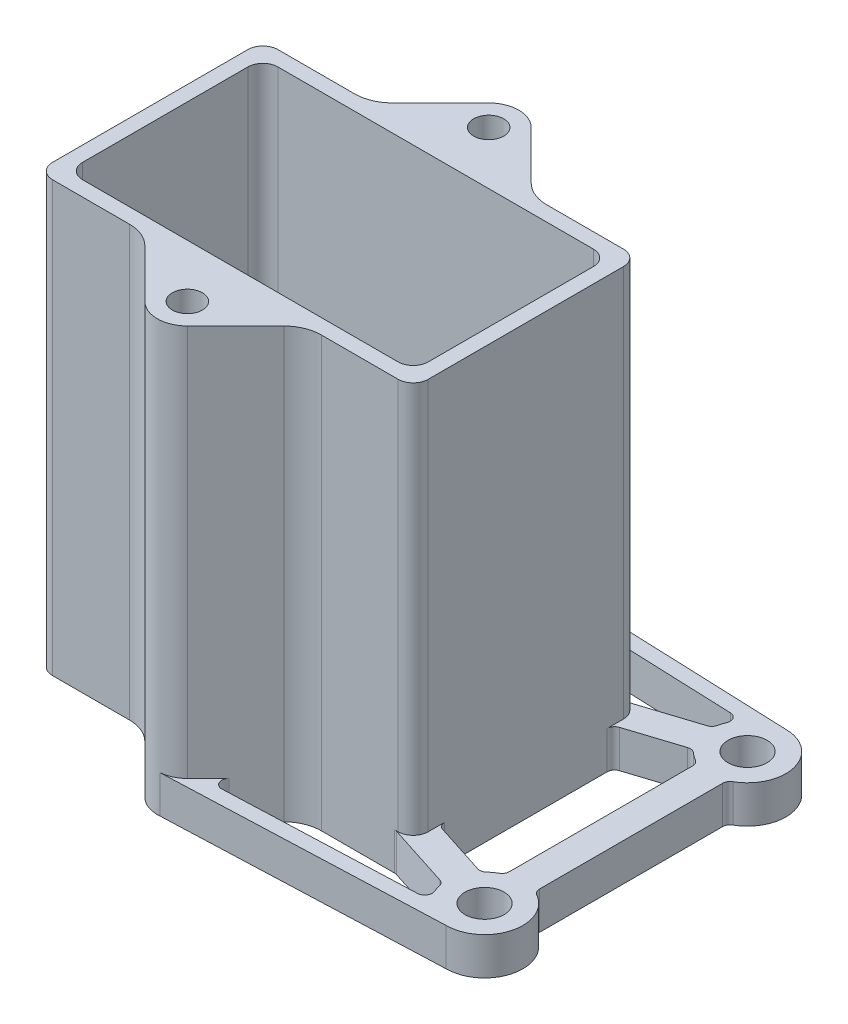
SolidWorks part; units mm, degrees
ref_plane "Front Plane" through (0, 0, 0) normal (0, 0, 1) x (1, 0, 0)
ref_plane "Top Plane" through (0, 0, 0) normal (0, 1, 0) x (1, 0, 0)
ref_plane "Right Plane" through (0, 0, 0) normal (1, 0, 0) x (0, 0, -1)
sketch "Sketch1" plane through (0, 0, 0) normal (0, 1, 0) x (1, 0, 0)
  line L1 (-25, -15) -> (25, -15)
  line L2 (-25, -15) -> (-25, 15)
  line L3 (-25, 15) -> (25, 15)
  line L4 (25, -15) -> (25, 15)
  line L5 (-25, -15) -> (25, 15) construction
  line L6 (-25, 15) -> (25, -15) construction
  point P0 (0, 0)
  dimension "D1" = 30
  dimension "D2" = 50
extrude "Boss-Extrude1" add sketch "Sketch1" along normal blind 3
sketch "Sketch2" plane through (0, 3, 0) normal (0, 1, 0) x (1, 0, 0)
  line L0 (23, -13) -> (23, 13)
  line L1 (23, 13) -> (-23, 13)
  line L2 (-23, 13) -> (-23, -13)
  line L3 (-23, -13) -> (23, -13)
  line L4 (25, -15) -> (25, 15)
  line L5 (25, 15) -> (-25, 15)
  line L6 (-25, 15) -> (-25, -15)
  line L7 (-25, -15) -> (25, -15)
  line L8 (25, -15) -> (25, 15)
  line L9 (25, 15) -> (-25, 15)
  line L10 (-25, 15) -> (-25, -15)
  line L11 (-25, -15) -> (25, -15)
  dimension "D1" = 0
  dimension "D2" = 2
extrude "Boss-Extrude2" add sketch "Sketch2" along normal blind 54.15
sketch "Sketch3" plane through (0, 0, 0) normal (0, 1, 0) x (1, 0, 0)
  line L0 (0, 0) -> (0, 20.05) construction
  line L1 (-2.8284, 22.8784) -> (-10.7069, 15)
  line L2 (-10.7069, 15) -> (10.7069, 15)
  line L3 (10.7069, 15) -> (2.8284, 22.8784)
  line L4 (25, -15) -> (25, 15)
  line L5 (-25, -15) -> (25, -15)
  line L6 (-25, 15) -> (-25, -15)
  line L7 (25, 15) -> (-25, 15)
  line L8 (25, -15) -> (25, 15)
  line L9 (-25, -15) -> (25, -15)
  line L10 (-25, 15) -> (-25, -15)
  line L11 (25, 15) -> (-25, 15)
  arc A0 (2.8284, 22.8784) -> (-2.8284, 22.8784) centre (0, 20.05) ccw
  circle A1 centre (0, 20.05) radius 2
  dimension "D3" = 2
  dimension "D4" = 4
  dimension "D2" = 45
  dimension "D5" = 20.05
  dimension "D1" = 0
extrude "Boss-Extrude3" add sketch "Sketch3" along direction (0, -1, 0) on the side of the normal up to surface (57.15 mm away)
mirror "Mirror1" about plane through (0, 0, 0) normal (0, 0, 1) of "Boss-Extrude3"
fillet "Fillet1" radius 2 8 edges at (23, 30.075, 13) (23, 30.075, -13) (-23, 30.075, -13) (-23, 30.075, 13) (25, 28.575, 15) (-25, 28.575, 15) (-25, 28.575, -15) (25, 28.575, -15)
sketch "Sketch4" plane through (-25, 0, 0) normal (-1, 0, 0) x (0, 0, 1)
  circle A0 centre (0, 12.7) radius 5
  point P2 (0, 0)
  dimension "D2" = 10
  dimension "D1" = 12.7
extrude "Cut-Extrude1" cut sketch "Sketch4" against normal up to surface (2 mm away) up to face at (-23, 30.075, 0)
sketch "Sketch5" plane through (0, 0, 0) normal (0, 1, 0) x (1, 0, 0)
  line L0 (0, 0) -> (37, 0) construction
  line L1 (37, 0) -> (37, 17.5) construction
  line L2 (37, 22.6) -> (0, 24.05)
  line L3 (39, -12.8085) -> (39, 12.8085)
  line L4 (37, -22.6) -> (0, -24.05)
  line L5 (3.8076, 21.8992) -> (33.0717, 20.7524)
  line L6 (3.8076, -21.8992) -> (33.0717, -20.7524)
  line L7 (35, -12.8085) -> (35, 12.8085)
  line L8 (23, 13) -> (37, 17.5) construction
  line L9 (23, -13) -> (37, -17.5) construction
  line L10 (22.6865, 15) -> (31.9216, 17.9684)
  line L11 (25, 11.5421) -> (33.1456, 14.1603)
  line L12 (25, -11.5421) -> (33.1456, -14.1603)
  line L13 (22.6865, -15) -> (31.9216, -17.9684)
  line L15 (-23, -15) -> (-10.7069, -15)
  line L16 (-25, 13) -> (-25, -13)
  line L17 (-10.7069, 15) -> (-23, 15)
  line L18 (-2.8284, 22.8784) -> (-10.7069, 15)
  line L19 (10.7069, 15) -> (2.8284, 22.8784)
  line L20 (23, 15) -> (10.7069, 15)
  line L21 (25, -13) -> (25, 13)
  line L22 (10.7069, -15) -> (23, -15)
  line L23 (2.8284, -22.8784) -> (10.7069, -15)
  line L24 (-10.7069, -15) -> (-2.8284, -22.8784)
  line L25 (-23, -15) -> (-10.7069, -15)
  line L26 (-25, 13) -> (-25, -13)
  line L27 (-10.7069, 15) -> (-23, 15)
  line L28 (-2.8284, 22.8784) -> (-10.7069, 15)
  line L29 (10.7069, 15) -> (2.8284, 22.8784)
  line L30 (23, 15) -> (10.7069, 15)
  line L31 (25, -13) -> (25, 13)
  line L32 (10.7069, -15) -> (23, -15)
  line L33 (2.8284, -22.8784) -> (10.7069, -15)
  line L34 (-10.7069, -15) -> (-2.8284, -22.8784)
  circle A0 centre (37, 17.5) radius 2.6
  circle A1 centre (37, -17.5) radius 2.6
  circle A2 centre (37, 17.5) radius 5.1
  circle A3 centre (37, -17.5) radius 5.1
  arc A4 (2.8284, 22.8784) -> (-2.8284, 22.8784) centre (0, 20.05) ccw construction
  arc A5 (-2.8284, -22.8784) -> (2.8284, -22.8784) centre (0, -20.05) ccw construction
  arc A12 (-25, -13) -> (-23, -15) centre (-23, -13) ccw
  arc A13 (-23, 15) -> (-25, 13) centre (-23, 13) ccw
  arc A14 (2.8284, 22.8784) -> (-2.8284, 22.8784) centre (0, 20.05) ccw
  arc A15 (25, 13) -> (23, 15) centre (23, 13) ccw
  arc A16 (23, -15) -> (25, -13) centre (23, -13) ccw
  arc A17 (-2.8284, -22.8784) -> (2.8284, -22.8784) centre (0, -20.05) ccw
  arc A18 (-25, -13) -> (-23, -15) centre (-23, -13) ccw
  arc A19 (-23, 15) -> (-25, 13) centre (-23, 13) ccw
  arc A20 (2.8284, 22.8784) -> (-2.8284, 22.8784) centre (0, 20.05) ccw
  arc A21 (25, 13) -> (23, 15) centre (23, 13) ccw
  arc A22 (23, -15) -> (25, -13) centre (23, -13) ccw
  arc A23 (-2.8284, -22.8784) -> (2.8284, -22.8784) centre (0, -20.05) ccw
  point P51 (0, 0)
  dimension "D2" = 5.2
  dimension "D3" = 2.5
  dimension "D1" = 35
  dimension "D4" = 12
  dimension "D6" = 2
  dimension "D7" = 4
  dimension "D8" = 4
  dimension "D5" = 0
extrude "Boss-Extrude4" add sketch "Sketch5" along normal blind 5 contours A20 L29 L5 A2 L2 | A21 L31 L11 A2 L10 L30 | A2 L2 A0 | A3 L3 A2 L7 | A22 L32 L13 A3 L12 L31 | L4 A3 A1 | A23 L4 A3 L6 L33
fillet "Fillet2" radius 1 16 edges at (35, 2.5, -12.8085) (33.1456, 2.5, -14.1603) (22.6865, 2.5, 15) (33.0717, 2.5, 20.7524) (31.9216, 2.5, 17.9684) (35, 2.5, 12.8085) (33.1456, 2.5, 14.1603) (3.8076, 2.5, 21.8992) (3.8076, 2.5, -21.8992) (31.9216, 2.5, -17.9684) (33.0717, 2.5, -20.7524) (22.6865, 2.5, -15) (25, 2.5, -11.5421) (25, 2.5, 11.5421) (39, 2.5, 12.8085) (39, 2.5, -12.8085)
fillet "Fillet3" radius 5 4 edges at (10.7069, 28.575, 15) (-10.7069, 28.575, 15) (-10.7069, 28.575, -15) (10.7069, 28.575, -15)
